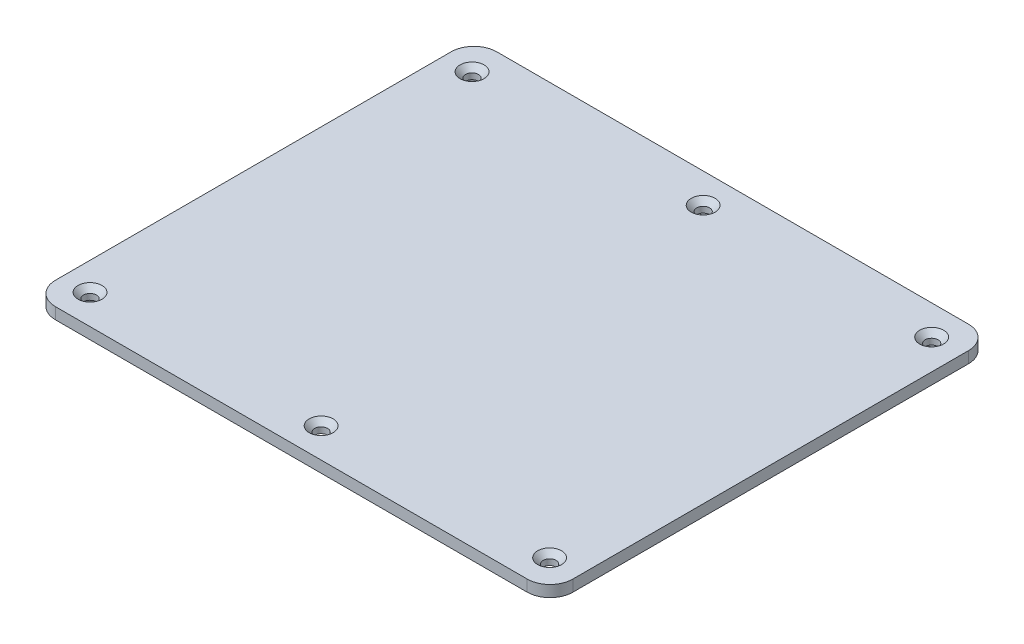
SolidWorks part; units mm, degrees
material "PET"
ref_plane "Front Plane" through (0, 0, 0) normal (0, 0, 1) x (1, 0, 0)
ref_plane "Top Plane" through (0, 0, 0) normal (0, 1, 0) x (1, 0, 0)
ref_plane "Right Plane" through (0, 0, 0) normal (1, 0, 0) x (0, 0, -1)
sketch "Sketch1" plane through (0, 0, 0) normal (0, 1, 0) x (1, 0, 0)
  line L1 (62, -58) -> (-62, -58)
  line L2 (68, -52) -> (68, 52)
  line L3 (62, 58) -> (-62, 58)
  line L4 (-68, -52) -> (-68, 52)
  line L5 (68, -58) -> (-68, 58) construction
  line L6 (68, 58) -> (-68, -58) construction
  arc A0 (-68, -52) -> (-62, -58) centre (-62, -52) ccw
  arc A1 (62, -58) -> (68, -52) centre (62, -52) ccw
  arc A2 (68, 52) -> (62, 58) centre (62, 52) ccw
  arc A3 (-62, 58) -> (-68, 52) centre (-62, 52) ccw
  point P0 (0, 0)
  dimension "D3" = 6
  dimension "D1" = 136
  dimension "D2" = 116
extrude "Boss-Extrude1" add sketch "Sketch1" along normal blind 3
sketch "Sketch2" plane through (0, 3, 0) normal (0, 1, 0) x (1, 0, 0)
  line L0 (-68, 52) -> (-68, -52) construction
  line L1 (-61.84, 54.84) -> (61.84, 54.84)
  line L2 (-64.84, 51.84) -> (-64.84, -51.84)
  line L3 (-61.84, -54.84) -> (61.84, -54.84)
  line L4 (64.84, 51.84) -> (64.84, -51.84)
  line L5 (62, 58) -> (-62, 58) construction
  line L6 (-62, -58) -> (62, -58) construction
  line L7 (68, -52) -> (68, 52) construction
  line L8 (-62.84, 49.84) -> (-62.84, -49.84)
  line L9 (-59.84, -52.84) -> (59.84, -52.84)
  line L10 (62.84, 49.84) -> (62.84, -49.84)
  line L11 (-59.84, 52.84) -> (59.84, 52.84)
  line L12 (-62.84, 52.84) -> (-62.84, -52.84) construction
  line L13 (-62.84, -52.84) -> (62.84, -52.84) construction
  line L14 (-64.84, 54.84) -> (-64.84, -54.84) construction
  line L15 (-64.84, -54.84) -> (64.84, -54.84) construction
  line L16 (62.84, 52.84) -> (62.84, -52.84) construction
  line L17 (64.84, 54.84) -> (64.84, -54.84) construction
  line L18 (-62.84, 52.84) -> (62.84, 52.84) construction
  line L19 (-64.84, 54.84) -> (64.84, 54.84) construction
  arc A0 (-62.84, -49.84) -> (-59.84, -52.84) centre (-59.84, -49.84) ccw
  arc A1 (-64.84, -51.84) -> (-61.84, -54.84) centre (-61.84, -51.84) ccw
  arc A2 (59.84, -52.84) -> (62.84, -49.84) centre (59.84, -49.84) ccw
  arc A3 (61.84, -54.84) -> (64.84, -51.84) centre (61.84, -51.84) ccw
  arc A4 (62.84, 49.84) -> (59.84, 52.84) centre (59.84, 49.84) ccw
  arc A5 (61.84, 54.84) -> (64.84, 51.84) centre (61.84, 51.84) cw
  arc A6 (-62.84, 49.84) -> (-59.84, 52.84) centre (-59.84, 49.84) cw
  arc A7 (-61.84, 54.84) -> (-64.84, 51.84) centre (-61.84, 51.84) ccw
  dimension "D6" = 3
  dimension "D1" = 3.16
  dimension "D2" = 3.16
  dimension "D3" = 3.16
  dimension "D4" = 3.16
  dimension "D5" = 2
extrude "Boss-Extrude2" add sketch "Sketch2" against normal blind 5
sketch "Sketch3" plane through (0, 3, 0) normal (0, 1, 0) x (1, 0, 0)
  line L0 (-68, 52) -> (-68, -52) construction
  line L1 (62, 58) -> (-62, 58) construction
  line L2 (68, -52) -> (68, 52) construction
  line L3 (-62, -58) -> (62, -58) construction
  circle A0 centre (-60.7, 50.2) radius 1.75
  circle A1 centre (0.04, 50.2) radius 1.75
  circle A2 centre (60.09, 50.2) radius 1.75
  circle A3 centre (-60.7, -50.2) radius 1.75
  circle A4 centre (0.04, -50.2) radius 1.75
  circle A5 centre (60.09, -50.2) radius 1.75
  point P20 (0, 0)
  dimension "D1" = 3.5
  dimension "D6" = 7.3
  dimension "D10" = 7.8
  dimension "D2" = 7.3
  dimension "D3" = 7.8
  dimension "D4" = 7.8
  dimension "D5" = 7.8
  dimension "D7" = 7.91
  dimension "D8" = 7.8
  dimension "D9" = 7.8
  dimension "D11" = 68.04
  dimension "D12" = 7.91
  dimension "D13" = 7.91
  dimension "D14" = 60.05
  dimension "D15" = 60.05
  dimension "D16" = 68.04
hole_wizard "CSK for M3 Countersunk Flat Head Screw1" positions "3DSketch1" profile "Sketch4" countersink size "M3" standard "ISO"
sketch3d "3DSketch1"
  line L0 (-68, 3, -52) -> (-68, 3, 52) construction
  line L1 (-62, 3, 58) -> (62, 3, 58) construction
  line L2 (68, 3, 52) -> (68, 3, -52) construction
  point P0 (-60.7, 3, -50.2)
  point P3 (0.04, 3, -50.2)
  point P6 (60.09, 3, -50.2)
  point P9 (-60.7, 3, 50.2)
  point P12 (0.04, 3, 50.2)
  point P15 (60.09, 3, 50.2)
  point P18 (-60.7, 3, 50.2)
  point P20 (-60.7, 3, -50.2)
  point P22 (0.04, 3, 50.2)
  point P24 (60.09, 3, 50.2)
  point P26 (60.09, 3, -50.2)
  point P28 (0.04, 3, -50.2)
  dimension "D1" = 7.3
  dimension "D2" = 68.04
  dimension "D3" = 7.8
  dimension "D4" = 7.8
  dimension "D5" = 7.8
  dimension "D6" = 7.3
  dimension "D7" = 7.91
  dimension "D8" = 7.91
  dimension "D9" = 68.04
sketch "Sketch4" plane through (-60.7, 3, -50.2) normal (1, 0, 0) x (0, 0, 1)
  line L0 (0, 0) -> (0, 7.0215)
  line L1 (0, 7.0215) -> (1.7, 6)
  line L2 (1.7, 6) -> (1.7, 1.45)
  line L3 (1.7, 1.45) -> (3.15, 0)
  line L5 (3.15, 0) -> (0, 0)
  line L6 (-1.7, 1.45) -> (-3.15, 0) construction
  line L10 (0, 7.0215) -> (-1.7, 6) construction
  line L11 (0, -6.35) -> (0, 107.95) construction
  dimension "Hole Dia." = 3.4
  dimension "Hole Depth" = 6
  dimension "Near C'Sink Dia." = 6.3
  dimension "Near C'Sink Angle" = 90
  dimension "Drill Angle" = 118
